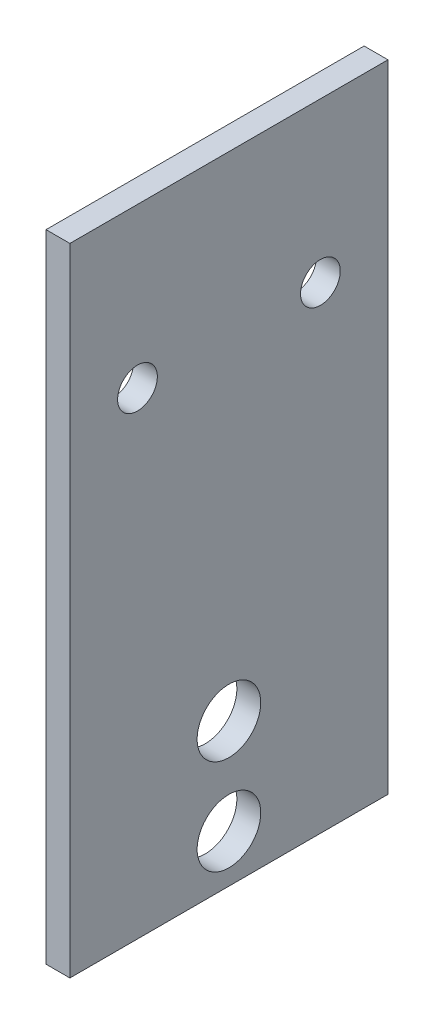
SolidWorks part; units mm, degrees
ref_plane "Front Plane" through (0, 0, 0) normal (0, 0, 1) x (1, 0, 0)
ref_plane "Top Plane" through (0, 0, 0) normal (0, 1, 0) x (1, 0, 0)
ref_plane "Right Plane" through (0, 0, 0) normal (1, 0, 0) x (0, 0, -1)
sketch "Sketch1" plane through (0, 0, 0) normal (1, 0, 0) x (0, 0, -1)
  line L1 (-20, -40) -> (20, -40)
  line L2 (-20, -40) -> (-20, 40)
  line L3 (-20, 40) -> (20, 40)
  line L4 (20, -40) -> (20, 40)
  line L5 (-20, -40) -> (20, 40) construction
  line L6 (-20, 40) -> (20, -40) construction
  point P0 (0, 0)
  dimension "D1" = 40
  dimension "D2" = 80
extrude "Boss-Extrude1" add sketch "Sketch1" along normal blind 3
sketch "Sketch2" plane through (3, 0, 0) normal (1, 0, 0) x (0, 0, -1)
  line L0 (-20, -40) -> (20, -40) construction
  circle A0 centre (0, -22) radius 4
  circle A1 centre (0, -34) radius 4
  circle A2 centre (-11.5, 20) radius 2.5
  circle A3 centre (11.5, 20) radius 2.5
  point P11 (0, 0)
  point P12 (0, 0)
  dimension "D1" = 8
  dimension "D2" = 6
  dimension "D3" = 12
  dimension "D4" = 5
  dimension "D5" = 23
  dimension "D6" = 11.5
  dimension "D7" = 20
extrude "Cut-Extrude1" cut sketch "Sketch2" against normal through all
